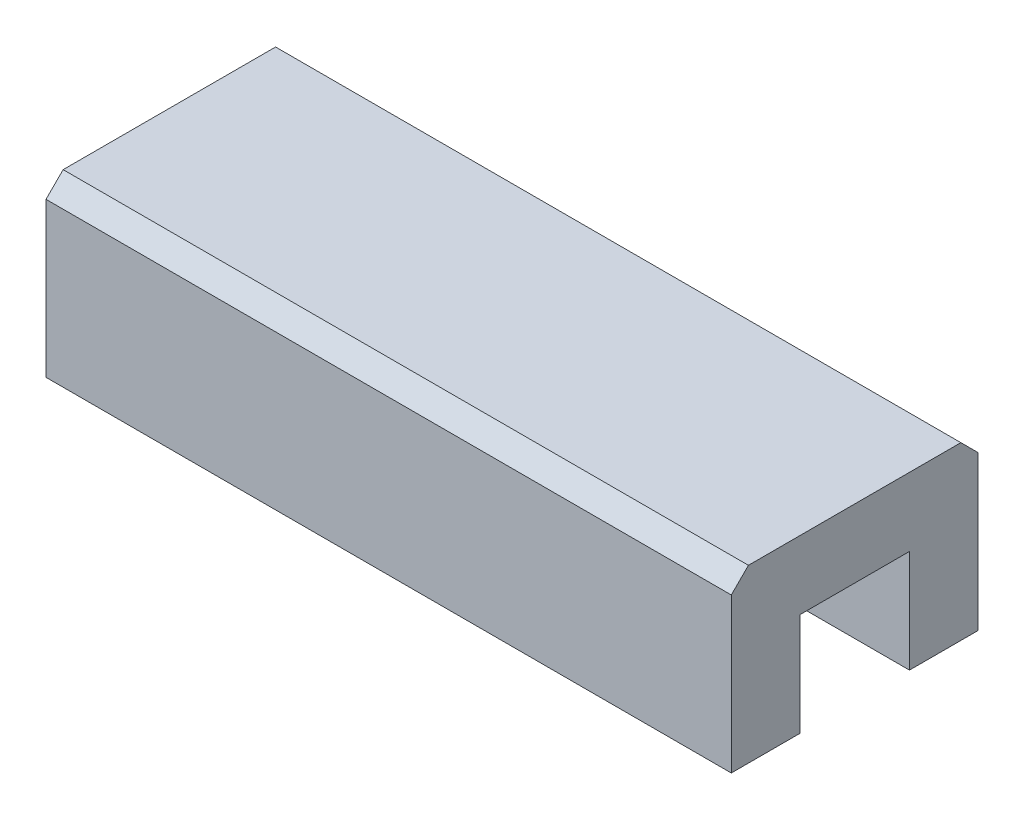
SolidWorks part; units mm, degrees
ref_plane "Front Plane" through (0, 0, 0) normal (0, 0, 1) x (1, 0, 0)
ref_plane "Top Plane" through (0, 0, 0) normal (0, 1, 0) x (1, 0, 0)
ref_plane "Right Plane" through (0, 0, 0) normal (1, 0, 0) x (0, 0, -1)
sketch "Sketch2" plane through (0, 0, 0) normal (0, 0, 1) x (1, 0, 0)
  line L1 (-10, -2.5) -> (10, -2.5)
  line L2 (-10, -2.5) -> (-10, 2.5)
  line L3 (-10, 2.5) -> (10, 2.5)
  line L4 (10, -2.5) -> (10, 2.5)
  line L5 (-10, -2.5) -> (10, 2.5) construction
  line L6 (-10, 2.5) -> (10, -2.5) construction
  point P0 (0, 0)
  dimension "D1" = 20
  dimension "D2" = 5
extrude "Boss-Extrude1" add sketch "Sketch2" along normal blind 7.2
sketch "Sketch3" plane through (10, 0, 0) normal (1, 0, 0) x (0, 0, -1)
  line L0 (-7.2, -2.5) -> (0, -2.5) construction
  line L1 (-5.2, -2.5) -> (-2, -2.5)
  line L2 (-5.2, -2.5) -> (-5.2, 0.5)
  line L3 (-5.2, 0.5) -> (-2, 0.5)
  line L4 (-2, -2.5) -> (-2, 0.5)
  line L5 (-7.2, -2.5) -> (-7.2, 2.5) construction
  line L6 (-7.2, 2.5) -> (0, 2.5) construction
  point P4 (-3.6, -2.5)
  point P5 (0, 0)
  dimension "D1" = 2
  dimension "D2" = 2
extrude "Cut-Extrude1" cut sketch "Sketch3" against normal up to next
chamfer "Chamfer1" distance 0.5 angle 45 2 edges at (0, 2.5, 7.2) (0, 2.5, 0)
